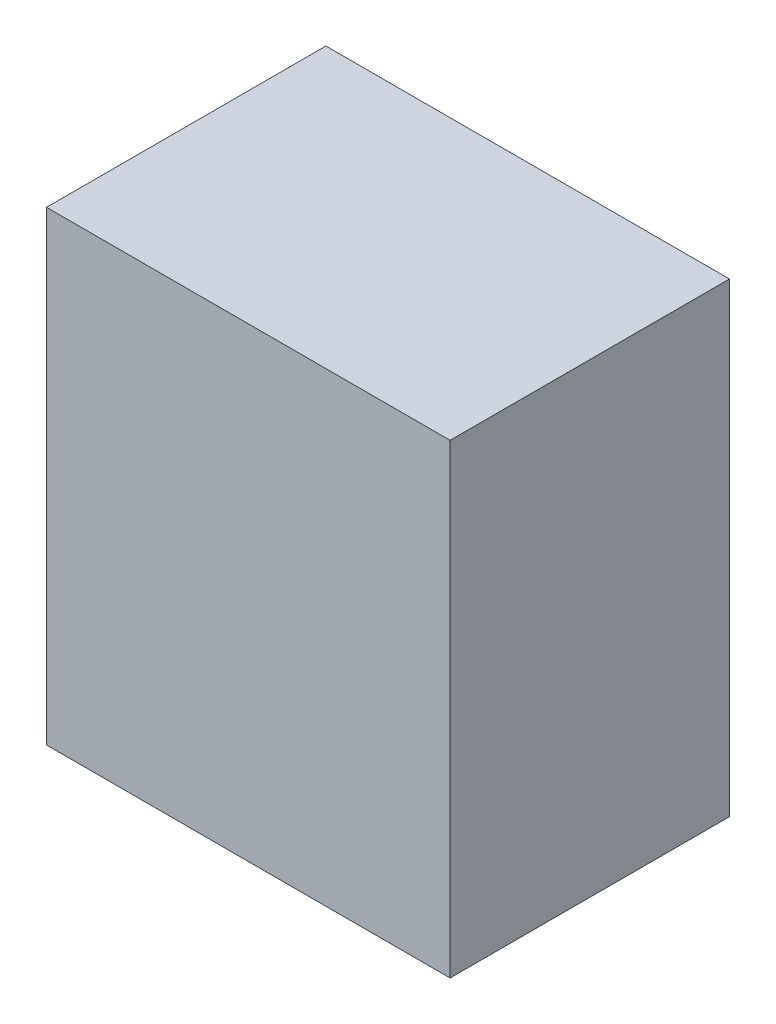
SolidWorks part; units mm, degrees
ref_plane "Front Plane" through (0, 0, 0) normal (0, 0, 1) x (1, 0, 0)
ref_plane "Top Plane" through (0, 0, 0) normal (0, 1, 0) x (1, 0, 0)
ref_plane "Right Plane" through (0, 0, 0) normal (1, 0, 0) x (0, 0, -1)
other "Configuration Table"
sketch "Sketch1" plane through (0, 0, 0) normal (0, 0, 1) x (1, 0, 0)
  line L1 (380, 1400) -> (640, 1400)
  line L2 (380, 1400) -> (380, 1700)
  line L3 (380, 1700) -> (640, 1700)
  line L4 (640, 1400) -> (640, 1700)
extrude "PRESS_kontrol_panosu_kucuk_1" add sketch "Sketch1" against normal blind 180 from offset 120 separate body
